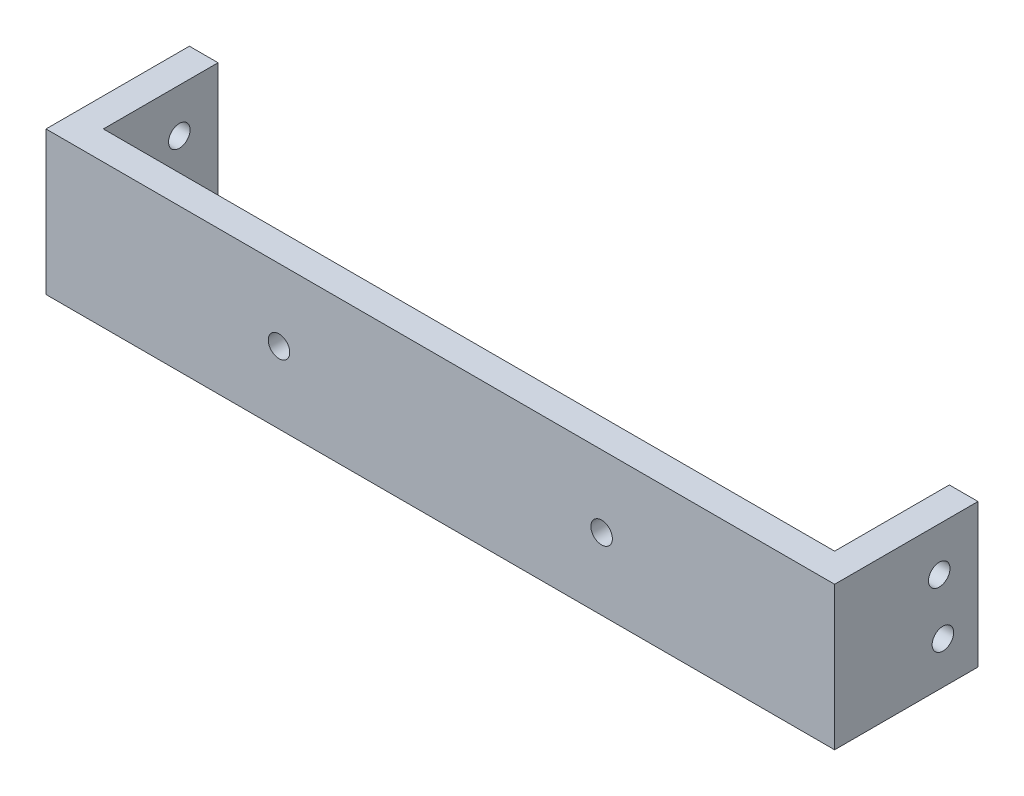
SolidWorks part; units mm, degrees
ref_plane "Front Plane" through (0, 0, 0) normal (0, 0, 1) x (1, 0, 0)
ref_plane "Top Plane" through (0, 0, 0) normal (0, 1, 0) x (1, 0, 0)
ref_plane "Right Plane" through (0, 0, 0) normal (1, 0, 0) x (0, 0, -1)
sketch "Sketch1" plane through (0, 0, 0) normal (0, 1, 0) x (1, 0, 0)
  line L1 (-55, 2) -> (55, 2)
  line L2 (-55, 2) -> (-55, -2)
  line L3 (-55, -2) -> (55, -2)
  line L4 (55, 2) -> (55, -2)
  line L5 (-55, 2) -> (55, -2) construction
  line L6 (-55, -2) -> (55, 2) construction
  line L7 (-55, 2) -> (-51, 2)
  line L8 (-55, 2) -> (-55, 18)
  line L9 (-55, 18) -> (-51, 18)
  line L10 (-51, 2) -> (-51, 18)
  line L11 (55, 2) -> (51, 2)
  line L12 (55, 2) -> (55, 18)
  line L13 (55, 18) -> (51, 18)
  line L14 (51, 2) -> (51, 18)
  point P0 (0, 0)
  dimension "D1" = 4
  dimension "D2" = 110
  dimension "D3" = 4
  dimension "D4" = 16
extrude "Boss-Extrude1" add sketch "Sketch1" along normal blind 20 contours L4 L1 L2 L3 | L1 L10 L9 L8 | L14 L1 L12 L13
sketch "Sketch2" plane through (55, 0, 0) normal (1, 0, 0) x (0, 0, -1)
  line L1 (-2, 20) -> (-2, 0) construction
  circle A0 centre (10.104, 5.883) radius 1.5 construction
  circle A1 centre (9.5936, 13.8673) radius 1.5 construction
  circle A4 centre (12.5936, 13.8673) radius 1.5
  circle A5 centre (13.104, 5.883) radius 1.5
  point P12 (0, 0)
  point P13 (0, 0)
  dimension "D1" = 3
  dimension "D2" = 11.5936
  dimension "D3" = 12.104
  dimension "D4" = 14.5936
  dimension "D5" = 15.104
extrude "Cut-Extrude1" cut sketch "Sketch2" against normal through all
sketch "Sketch3" plane through (0, 0, 2) normal (0, 0, 1) x (1, 0, 0)
  line L0 (0, 0) -> (0, 20) construction
  line L1 (-55, 20) -> (55, 20) construction
  line L2 (22.5, 10) -> (-22.5, 10)
  circle A0 centre (22.5, 10) radius 1.5
  circle A1 centre (-22.5, 10) radius 1.5
  point P5 (0, 10)
  point P9 (0, 10)
  dimension "D2" = 3
  dimension "D1" = 45
extrude "Cut-Extrude2" cut sketch "Sketch3" against normal through all
equation "\"D4@Sketch2\"=\"D2@Sketch2\"+3"
equation "\"D5@Sketch2\"=\"D3@Sketch2\"+3"
